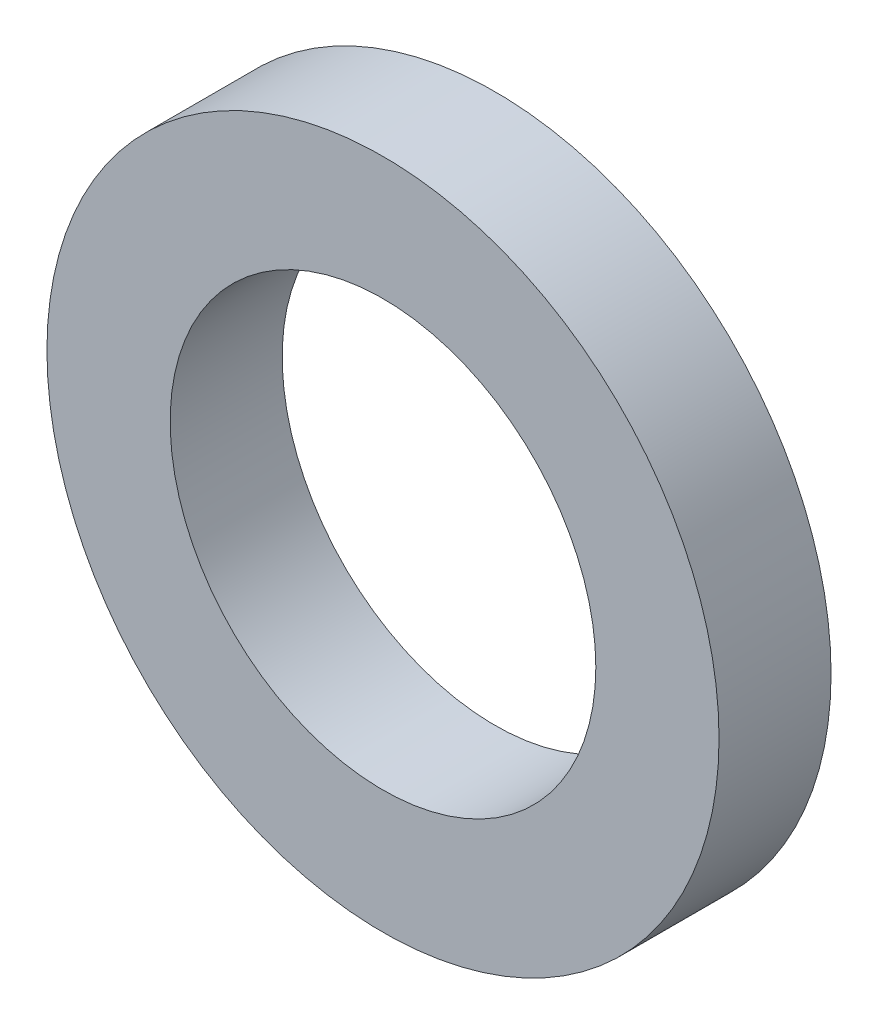
SolidWorks part; units mm, degrees
ref_plane "Front Plane" through (0, 0, 0) normal (0, 0, 1) x (1, 0, 0)
ref_plane "Top Plane" through (0, 0, 0) normal (0, 1, 0) x (1, 0, 0)
ref_plane "Right Plane" through (0, 0, 0) normal (1, 0, 0) x (0, 0, -1)
sketch "Sketch2" plane through (0, 0, 0) normal (0, 0, 1) x (1, 0, 0)
  circle A0 centre (0, 0) radius 3
  dimension "D1" = 6
extrude "Boss-Extrude1" add sketch "Sketch2" along normal blind 1
sketch "Sketch3" plane through (0, 0, 1) normal (0, 0, 1) x (1, 0, 0)
  circle A0 centre (0, 0) radius 1.9
  dimension "D1" = 3.8
extrude "Cut-Extrude1" cut sketch "Sketch3" against normal blind 1
